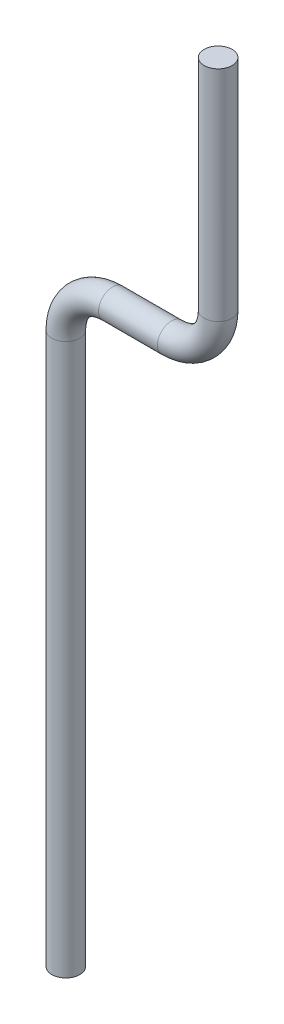
SolidWorks part; units mm, degrees
ref_plane "Front Plane" through (0, 0, 0) normal (0, 0, 1) x (1, 0, 0)
ref_plane "Top Plane" through (0, 0, 0) normal (0, 1, 0) x (1, 0, 0)
ref_plane "Right Plane" through (0, 0, 0) normal (1, 0, 0) x (0, 0, -1)
sketch "Sketch1" plane through (0, 0, 0) normal (0, 0, 1) x (1, 0, 0)
  line L0 (0, 0) -> (0, -23.4294)
  line L1 (-16.3048, -92.4319) -> (-16.3048, -33.4294)
  line L2 (-11.3048, -28.4294) -> (-5, -28.4294)
  arc A0 (0, -23.4294) -> (-5, -28.4294) centre (-5, -23.4294) cw
  arc A1 (-11.3048, -28.4294) -> (-16.3048, -33.4294) centre (-11.3048, -33.4294) ccw
  dimension "D1" = 5
sketch "Sketch2" plane through (0, 0, 0) normal (0, 1, 0) x (1, 0, 0)
  circle A0 centre (0, 0) radius 1.5
  dimension "D1" = 3
sweep "Sweep1" add profiles "Sketch2" path "Sketch1"
